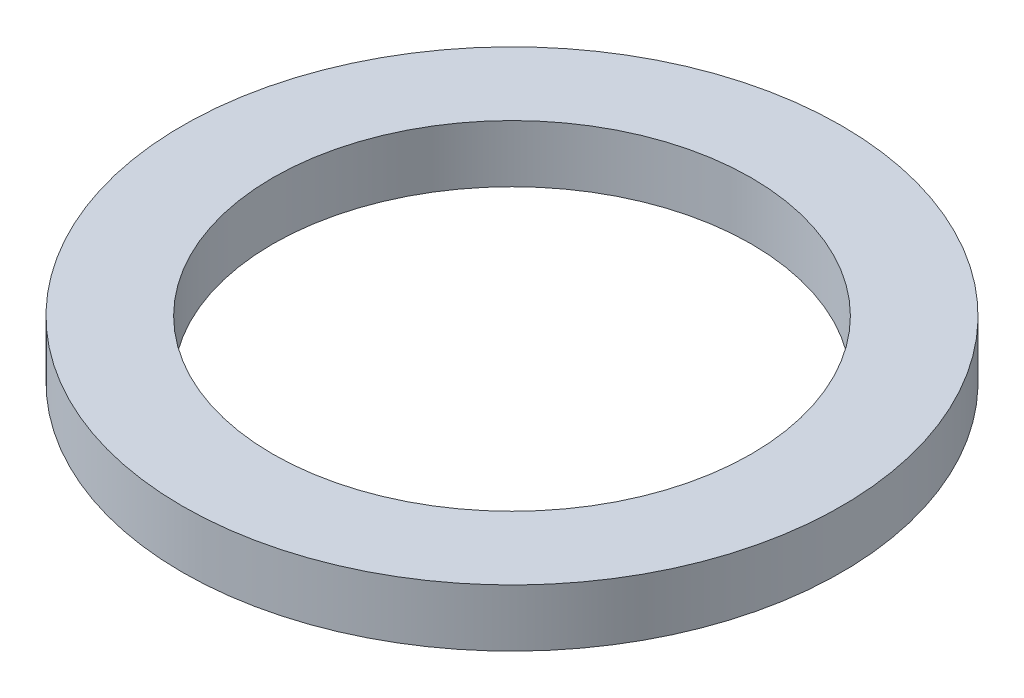
SolidWorks part; units mm, degrees
material "PLA плотность"
ref_plane "Спереди" through (0, 0, 0) normal (0, 0, 1) x (1, 0, 0)
ref_plane "Сверху" through (0, 0, 0) normal (0, 1, 0) x (1, 0, 0)
ref_plane "Справа" through (0, 0, 0) normal (1, 0, 0) x (0, 0, -1)
sketch "Эскиз1" plane through (0, 0, 0) normal (0, 1, 0) x (1, 0, 0)
  circle A0 centre (0, 0) radius 23
  circle A1 centre (0, 0) radius 16.7
  dimension "D1" = 46
  dimension "D2" = 33.4
extrude "Бобышка-Вытянуть1" add sketch "Эскиз1" along normal blind 4
